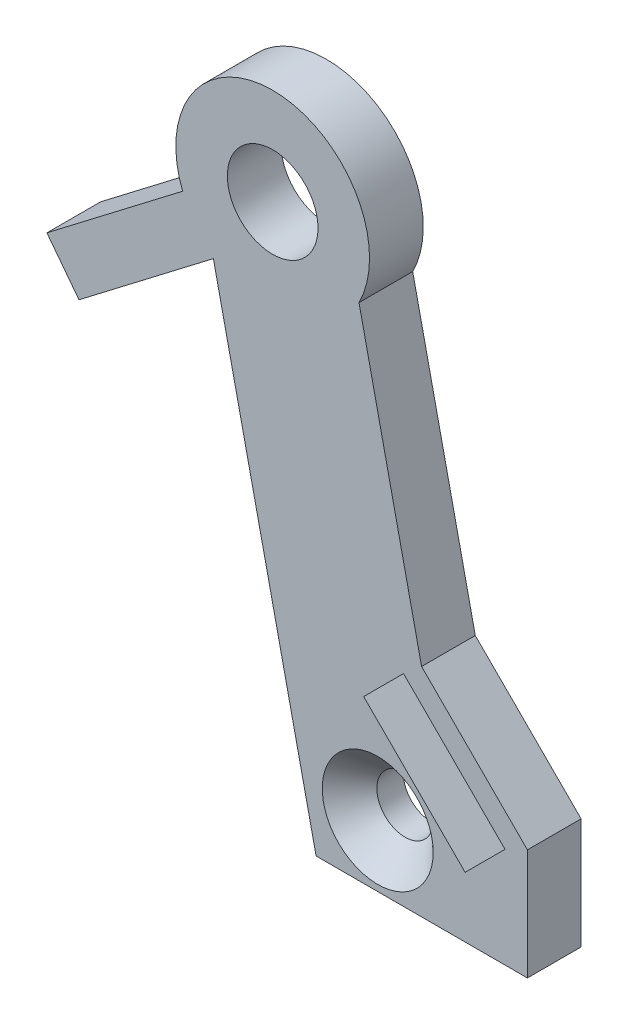
SolidWorks part; units mm, degrees
ref_plane "Front Plane" through (0, 0, 0) normal (0, 0, 1) x (1, 0, 0)
ref_plane "Top Plane" through (0, 0, 0) normal (0, 1, 0) x (1, 0, 0)
ref_plane "Right Plane" through (0, 0, 0) normal (1, 0, 0) x (0, 0, -1)
sketch "Sketch1" plane through (0, 0, 0) normal (0, 0, 1) x (1, 0, 0)
  line L0 (0, 12) -> (12, 0) construction
  line L1 (0, 0) -> (12, 0)
  line L2 (0, 0) -> (0, 12) construction
  line L3 (0, 12) -> (12, 12) construction
  line L4 (12, 0) -> (12, 12) construction
  line L5 (0, 0) -> (3.5, 0)
  line L6 (0, 0) -> (0, 3.5)
  line L7 (0, 3.5) -> (3.5, 3.5) construction
  line L8 (3.5, 0) -> (3.5, 3.5) construction
  line L9 (8.2662, 3.6278) -> (8.3192, 3.6808) construction
  line L10 (8.4645, 3.4295) -> (2.7015, 9.1924)
  line L11 (2.7015, 9.1924) -> (4.9643, 11.4551)
  line L12 (8.4645, 3.4295) -> (10.7272, 5.6922)
  line L13 (4.9643, 11.4551) -> (10.7272, 5.6922)
  line L14 (0, 0) -> (-6.6164, 30.0157)
  line L15 (-6.6164, 30.0157) -> (1.6843, 31.8454)
  line L16 (1.6843, 31.8454) -> (5.9896, 12.3143)
  line L17 (5.9896, 12.3143) -> (12, 6.3039)
  line L18 (12, 0) -> (8.5175, 3.4825)
  line L19 (12, 6.3039) -> (12, 0)
  line L20 (0, 0) -> (0, 40.9886) construction
  line L21 (-2.466, 30.9306) -> (-14.3773, 21.8135) construction
  line L22 (-13.4656, 20.6223) -> (-15.289, 23.0046)
  line L23 (-15.289, 23.0046) -> (-7.5797, 28.9055)
  line L24 (-13.4656, 20.6223) -> (-5.8335, 26.4641)
  circle A0 centre (3.5, 3.5) radius 1.5
  circle A1 centre (-2.466, 30.9306) radius 2.575
  circle A3 centre (-2.466, 30.9306) radius 5.5
  point P28 (-14.3773, 21.8135)
  dimension "D5" = 3
  dimension "D6" = 5.15
  dimension "D7" = 11
  dimension "D1" = 12
  dimension "D2" = 12
  dimension "D3" = 3.5
  dimension "D4" = 3.5
  dimension "D8" = 45
  dimension "D9" = 6.3039
  dimension "D10" = 90
  dimension "D11" = 90
  dimension "D12" = 20
  dimension "D13" = 8.5
  dimension "D14" = 3.2
  dimension "D15" = 8.15
  dimension "D16" = 0.075
  dimension "D17" = 4.925
  dimension "D18" = 8.5
  dimension "D19" = 65
  dimension "D20" = 90
  dimension "D21" = 3
  dimension "D22" = 15
extrude "Boss-Extrude1" add sketch "Sketch1" along normal blind 3.05 contours L15 A3 A1 | L15 A3 A1 | A3 L14 L2 L10 L11 L13 L3 L17 L16 | L17 L3 L13 L12 L0 L4 | A0 L8 L1 L0 L2 L7 | A0 L7 L2 L1 L8 | A3 L23 L22 L24 L14
hole_wizard "CSK for M3 Flat Head Machine Screw1" positions "Sketch2" profile "Sketch3" countersink size "M3" standard "ANSI Metric" end condition through all
sketch "Sketch2" plane through (0, 0, 3.05) normal (0, 0, 1) x (1, 0, 0)
  point P0 (3.5, 3.5)
sketch "Sketch3" plane through (3.5, 3.5, 3.05) normal (1, 0, 0) x (0, -1, 0)
  line L0 (0, 0) -> (0, 3.05)
  line L1 (0, 3.05) -> (1.6, 3.05)
  line L2 (1.6, 3.05) -> (1.6, 1.55)
  line L3 (1.6, 1.55) -> (3.15, 0)
  line L5 (3.15, 0) -> (0, 0)
  line L6 (-1.6, 1.55) -> (-3.15, 0) construction
  line L11 (0, -6.35) -> (0, 107.95) construction
  dimension "Thru Hole Dia." = 3.2
  dimension "Thru Hole Depth" = 3.05
  dimension "Near C'Sink Dia." = 6.3
  dimension "Near C'Sink Angle" = 90
